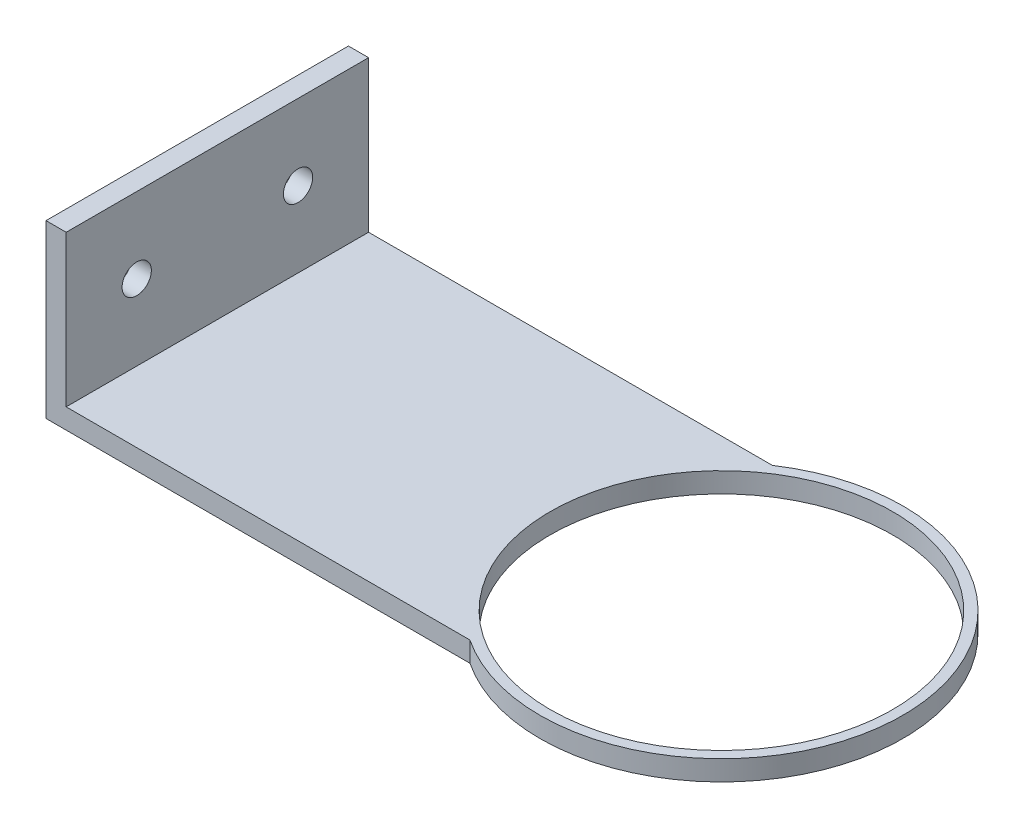
SolidWorks part; units mm, degrees
material "1.4511 (X3CrNb17)"
ref_plane "前视基准面" through (0, 0, 0) normal (0, 0, 1) x (1, 0, 0)
ref_plane "上视基准面" through (0, 0, 0) normal (0, 1, 0) x (1, 0, 0)
ref_plane "右视基准面" through (0, 0, 0) normal (1, 0, 0) x (0, 0, -1)
sketch "草图1" plane through (0, 0, 0) normal (0, 1, 0) x (1, 0, 0)
  line L4 (-52, 15) -> (-9.9499, 15)
  line L5 (-52, 15) -> (-52, -15)
  line L6 (-52, -15) -> (-9.9499, -15)
  circle A0 centre (0, 0) radius 18
  point P4 (0, 0)
  dimension "D1" = 36
  dimension "D2" = 30
  dimension "D4" = 52
extrude "凸台-拉伸1" add sketch "草图1" along normal blind 2
sketch "草图2" plane through (0, 2, 0) normal (0, 1, 0) x (1, 0, 0)
  line L0 (-52, 15) -> (-52, -15) construction
  line L1 (-52, 15) -> (-50, 15)
  line L2 (-52, 15) -> (-52, -15)
  line L3 (-52, -15) -> (-50, -15)
  line L4 (-50, 15) -> (-50, -15)
  line L5 (-52, 15) -> (-50, -15) construction
  line L6 (-52, -15) -> (-50, 15) construction
  point P6 (-52, 0)
  dimension "D1" = 2
  dimension "D2" = 30
extrude "凸台-拉伸2" add sketch "草图2" along normal blind 15
sketch "草图3" plane through (-50, 0, 0) normal (1, 0, 0) x (0, 0, -1)
  line L1 (-8, 9.5) -> (8, 9.5) construction
  line L2 (-15, 17) -> (15, 17) construction
  line L3 (-15, 17) -> (-15, 2) construction
  dimension "D1" = 16
  dimension "D2" = 7.5
  dimension "D3" = 7
hole_wizard "M3.5 螺纹孔1" positions "草图4" profile "草图5" tap size "M3.5" standard "GB" end condition through all
sketch "草图4" plane through (-50, 0, 0) normal (1, 0, 0) x (0, 0, -1)
  point P0 (-8, 9.5)
  point P3 (8, 9.5)
sketch "草图5" plane through (-50, 9.5, 8) normal (0, 1, 0) x (0, 0, -1)
  line L0 (0, 0) -> (0, 2)
  line L1 (0, 2) -> (1.45, 2)
  line L2 (1.45, 2) -> (1.45, 0)
  line L5 (1.45, 0) -> (0, 0)
  line L11 (0, -6.35) -> (0, 107.95) construction
  dimension "通孔螺纹孔钻头直径" = 2.9
  dimension "通孔螺纹孔钻头深度" = 2
cosmetic thread "孔螺蚊线1" parameters "D2"=3.5
cosmetic thread "孔螺蚊线2" parameters "D2"=3.5
sketch "草图6" plane through (0, 2, 0) normal (0, 1, 0) x (1, 0, 0)
  circle A0 centre (0, 0) radius 17
  dimension "D1" = 34
extrude "切除-拉伸1" cut sketch "草图6" against normal blind 15
